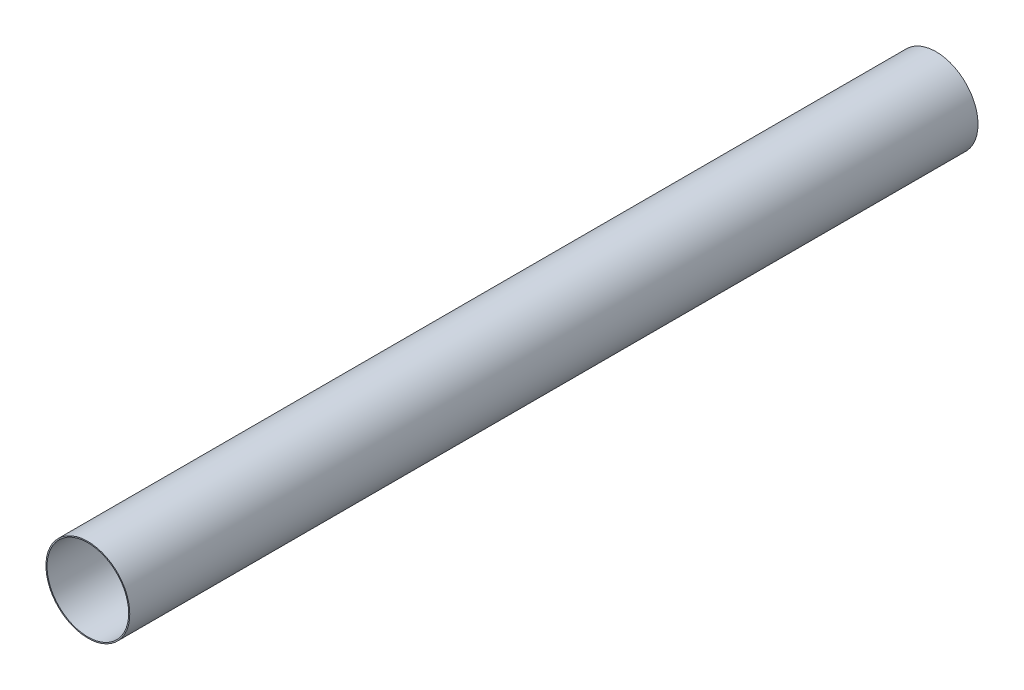
SolidWorks part; units mm, degrees
ref_plane "Front Plane" through (0, 0, 0) normal (0, 0, 1) x (1, 0, 0)
ref_plane "Top Plane" through (0, 0, 0) normal (0, 1, 0) x (1, 0, 0)
ref_plane "Right Plane" through (0, 0, 0) normal (1, 0, 0) x (0, 0, -1)
sketch "Sketch2" plane through (0, 0, 0) normal (0, 0, 1) x (1, 0, 0)
  circle A0 centre (0, 0) radius 55
  circle A1 centre (0, 0) radius 56.5
  dimension "D1" = 110
  dimension "D2" = 113
extrude "Boss-Extrude1" add sketch "Sketch2" along normal blind 1143
